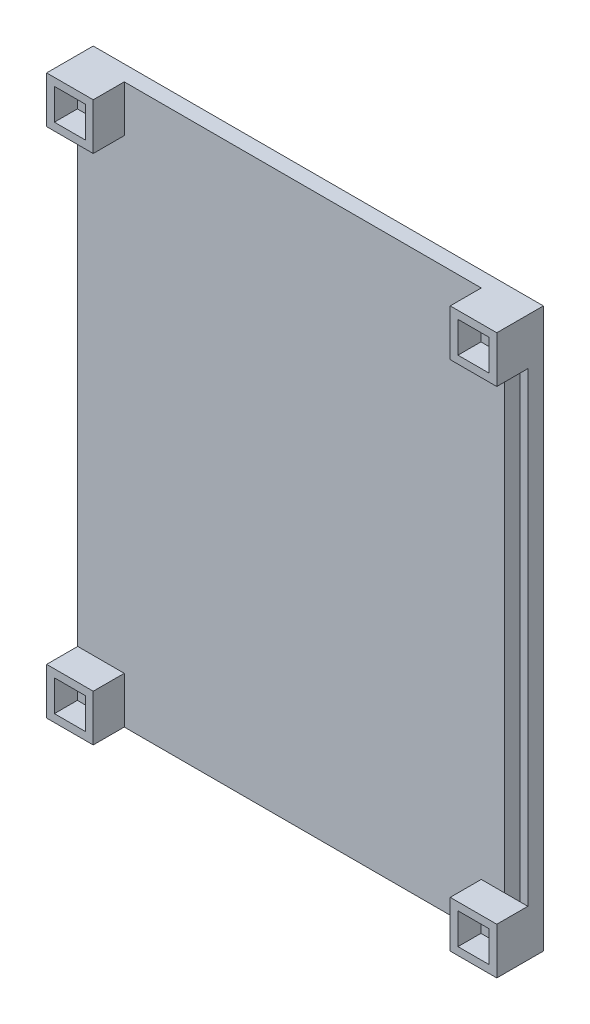
SolidWorks part; units mm, degrees
material "2024 Alloy"
ref_plane "Front Plane" through (0, 0, 0) normal (0, 0, 1) x (1, 0, 0)
ref_plane "Top Plane" through (0, 0, 0) normal (0, 1, 0) x (1, 0, 0)
ref_plane "Right Plane" through (0, 0, 0) normal (1, 0, 0) x (0, 0, -1)
sketch "Sketch1" plane through (0, 0, 0) normal (0, 0, 1) x (1, 0, 0)
  line L1 (-184.15, 228.6) -> (184.15, 228.6)
  line L2 (-184.15, 228.6) -> (-184.15, -228.6)
  line L3 (-184.15, -228.6) -> (184.15, -228.6)
  line L4 (184.15, 228.6) -> (184.15, -228.6)
  point P5 (-184.15, 0)
  point P7 (0, 228.6)
  dimension "D1" = 368.3
  dimension "D2" = 457.2
extrude "Boss-Extrude1" add sketch "Sketch1" along normal blind 12.7 contours L1 L4 L3 L2
sketch "Sketch2" plane through (0, 0, 12.7) normal (0, 0, 1) x (1, 0, 0)
  line L1 (-184.15, 228.6) -> (-146.05, 228.6)
  line L2 (-184.15, 228.6) -> (-184.15, 190.5)
  line L3 (-184.15, 190.5) -> (-146.05, 190.5)
  line L4 (-146.05, 228.6) -> (-146.05, 190.5)
  line L5 (-184.15, -228.6) -> (-146.05, -228.6)
  line L6 (-184.15, -228.6) -> (-184.15, -190.5)
  line L7 (-184.15, -190.5) -> (-146.05, -190.5)
  line L8 (-146.05, -228.6) -> (-146.05, -190.5)
  line L9 (184.15, -228.6) -> (146.05, -228.6)
  line L10 (184.15, -228.6) -> (184.15, -190.5)
  line L11 (184.15, -190.5) -> (146.05, -190.5)
  line L12 (146.05, -228.6) -> (146.05, -190.5)
  line L13 (184.15, 228.6) -> (146.05, 228.6)
  line L14 (184.15, 228.6) -> (184.15, 190.5)
  line L15 (184.15, 190.5) -> (146.05, 190.5)
  line L16 (146.05, 228.6) -> (146.05, 190.5)
  dimension "D1" = 38.1
extrude "Boss-Extrude2" add sketch "Sketch2" along normal blind 25.4
sketch "Sketch3" plane through (0, 0, 38.1) normal (0, 0, 1) x (1, 0, 0)
  line L14 (-177.8, 196.85) -> (-152.4, 196.85)
  line L15 (-177.8, 222.25) -> (-177.8, 196.85)
  line L16 (-152.4, 222.25) -> (-177.8, 222.25)
  line L17 (-152.4, 196.85) -> (-152.4, 222.25)
  line L18 (-177.8, 196.85) -> (-152.4, 196.85)
  line L19 (-177.8, 222.25) -> (-177.8, 196.85)
  line L20 (-152.4, 222.25) -> (-177.8, 222.25)
  line L21 (-152.4, 196.85) -> (-152.4, 222.25)
  line L28 (0, 0) -> (-184.15, 0) construction
  line L29 (-184.15, 190.5) -> (-184.15, -190.5) construction
  line L30 (152.4, -196.85) -> (177.8, -196.85)
  line L31 (152.4, -222.25) -> (152.4, -196.85)
  line L32 (177.8, 196.85) -> (177.8, 222.25)
  line L33 (177.8, 222.25) -> (152.4, 222.25)
  line L34 (152.4, 222.25) -> (152.4, 196.85)
  line L35 (152.4, 196.85) -> (177.8, 196.85)
  line L36 (177.8, 196.85) -> (177.8, 222.25)
  line L37 (177.8, 222.25) -> (152.4, 222.25)
  line L38 (152.4, 222.25) -> (152.4, 196.85)
  line L39 (152.4, 196.85) -> (177.8, 196.85)
  line L40 (177.8, -222.25) -> (152.4, -222.25)
  line L41 (177.8, -196.85) -> (177.8, -222.25)
  line L42 (-177.8, -222.25) -> (-177.8, -196.85)
  line L43 (-152.4, -222.25) -> (-177.8, -222.25)
  line L44 (-152.4, -196.85) -> (-152.4, -222.25)
  line L45 (-177.8, -196.85) -> (-152.4, -196.85)
  dimension "D1" = 6.35
  dimension "D2" = 6.35
extrude "Cut-Extrude1" cut sketch "Sketch3" against normal blind 18.796
sketch "Sketch4" plane through (0, 0, 0) normal (0, 0, -1) x (-1, 0, 0)
  line L0 (-184.15, 228.6) -> (-184.15, -228.6) construction
  line L1 (-177.8, -203.2) -> (-165.1, -203.2)
  line L2 (-177.8, -203.2) -> (-177.8, 203.2)
  line L3 (-177.8, 203.2) -> (-165.1, 203.2)
  line L4 (-165.1, -203.2) -> (-165.1, 203.2)
  line L5 (-177.8, -203.2) -> (-165.1, 203.2) construction
  line L6 (-177.8, 203.2) -> (-165.1, -203.2) construction
  line L7 (184.15, -228.6) -> (-184.15, -228.6) construction
  point P4 (-171.45, 0)
  dimension "D1" = 12.7
  dimension "D2" = 6.35
  dimension "D3" = 25.4
  dimension "D4" = 406.4
extrude "Cut-Extrude2" cut sketch "Sketch4" against normal blind 12.7
